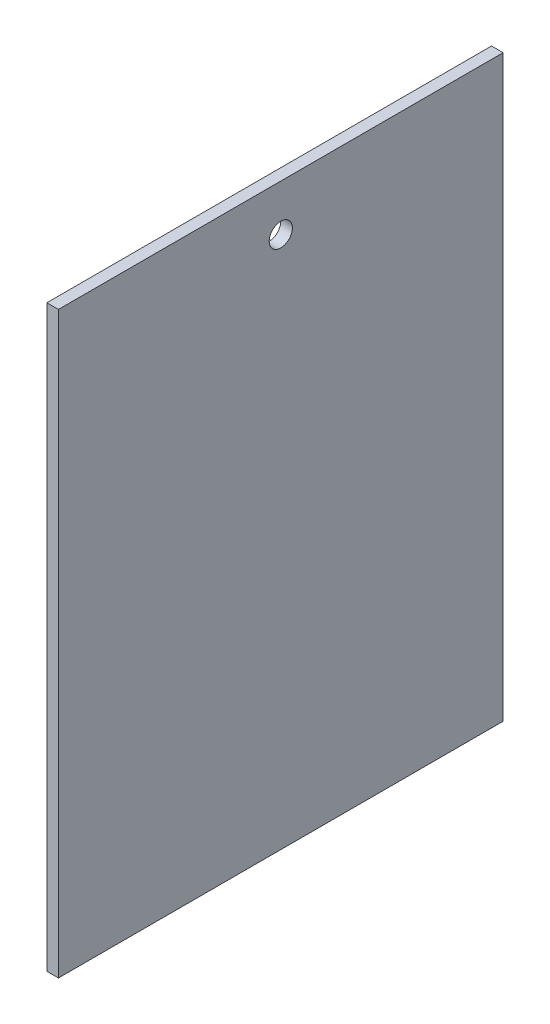
SolidWorks part; units mm, degrees
ref_plane "Front Plane" through (0, 0, 0) normal (0, 0, 1) x (1, 0, 0)
ref_plane "Top Plane" through (0, 0, 0) normal (0, 1, 0) x (1, 0, 0)
ref_plane "Right Plane" through (0, 0, 0) normal (1, 0, 0) x (0, 0, -1)
sketch "Sketch1" plane through (0, 0, 0) normal (1, 0, 0) x (0, 0, -1)
  line L1 (-192, 250) -> (192, 250)
  line L2 (-192, 250) -> (-192, -250)
  line L3 (-192, -250) -> (192, -250)
  line L4 (192, 250) -> (192, -250)
  line L5 (-192, 250) -> (192, -250) construction
  line L6 (-192, -250) -> (192, 250) construction
  point P0 (0, 0)
  dimension "D1" = 500
  dimension "D2" = 384
extrude "Boss-Extrude1" add sketch "Sketch1" along normal mid plane 10
sketch "Sketch2" plane through (5, 0, 0) normal (1, 0, 0) x (0, 0, -1)
  line L0 (192, 250) -> (-192, 250) construction
  circle A0 centre (0, 210) radius 10
  dimension "D1" = 20
  dimension "D2" = 40
extrude "Cut-Extrude1" cut sketch "Sketch2" against normal through all
